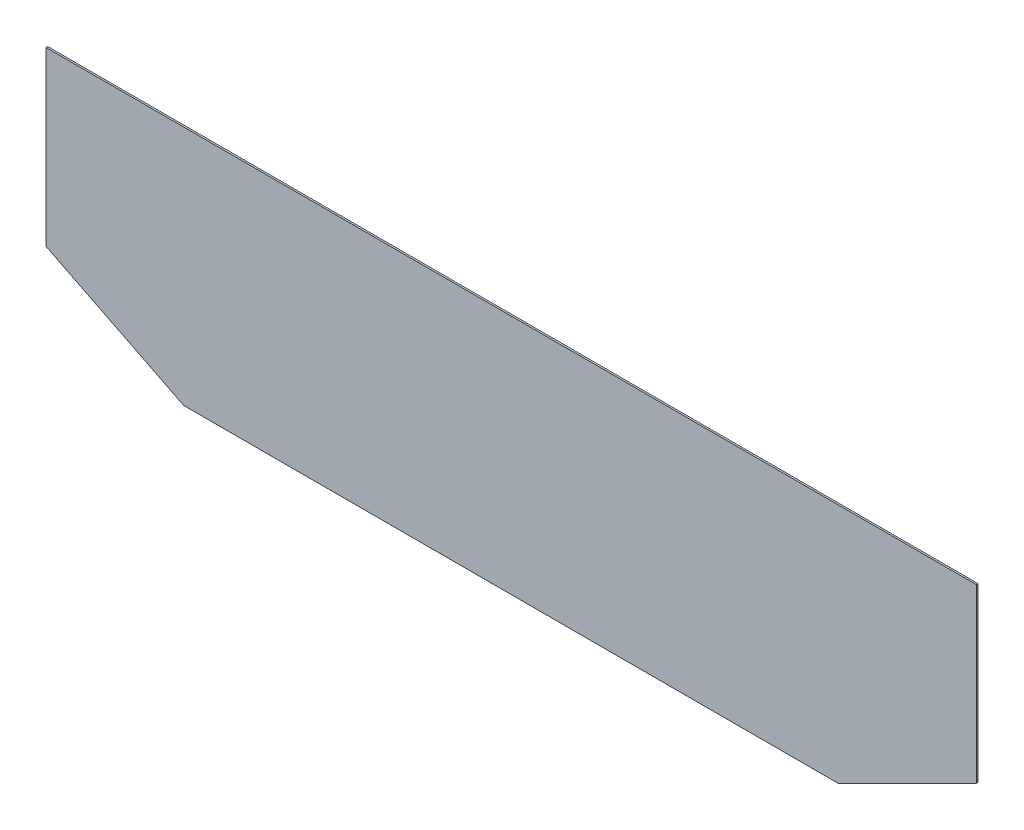
SolidWorks part; units mm, degrees
ref_plane "Plan de face" through (0, 0, 0) normal (0, 0, 1) x (1, 0, 0)
ref_plane "Plan de dessus" through (0, 0, 0) normal (0, 1, 0) x (1, 0, 0)
ref_plane "Plan de droite" through (0, 0, 0) normal (1, 0, 0) x (0, 0, -1)
sketch "Esquisse1" plane through (0, 0, 0) normal (0, 0, 1) x (1, 0, 0)
  line L0 (-195.2887, -15) -> (218.3694, -15) construction
  line L1 (-135, 35) -> (135, 35)
  line L2 (-135, 35) -> (-135, -35)
  line L3 (-135, -35) -> (135, -35)
  line L4 (135, 35) -> (135, -35)
  line L5 (-135, 35) -> (135, -35) construction
  line L6 (-135, -35) -> (135, 35) construction
  line L7 (135, -15) -> (95, -35)
  line L8 (-135, -15) -> (-95, -35)
  point P0 (0, 0)
  dimension "D1" = 270
  dimension "D2" = 70
  dimension "D3" = 50
  dimension "D4" = 40
  dimension "D5" = 40
extrude "Boss.-Extru.1" add sketch "Esquisse1" along normal blind 0.5 contours L2 L8 L3 L7 L4 L1
